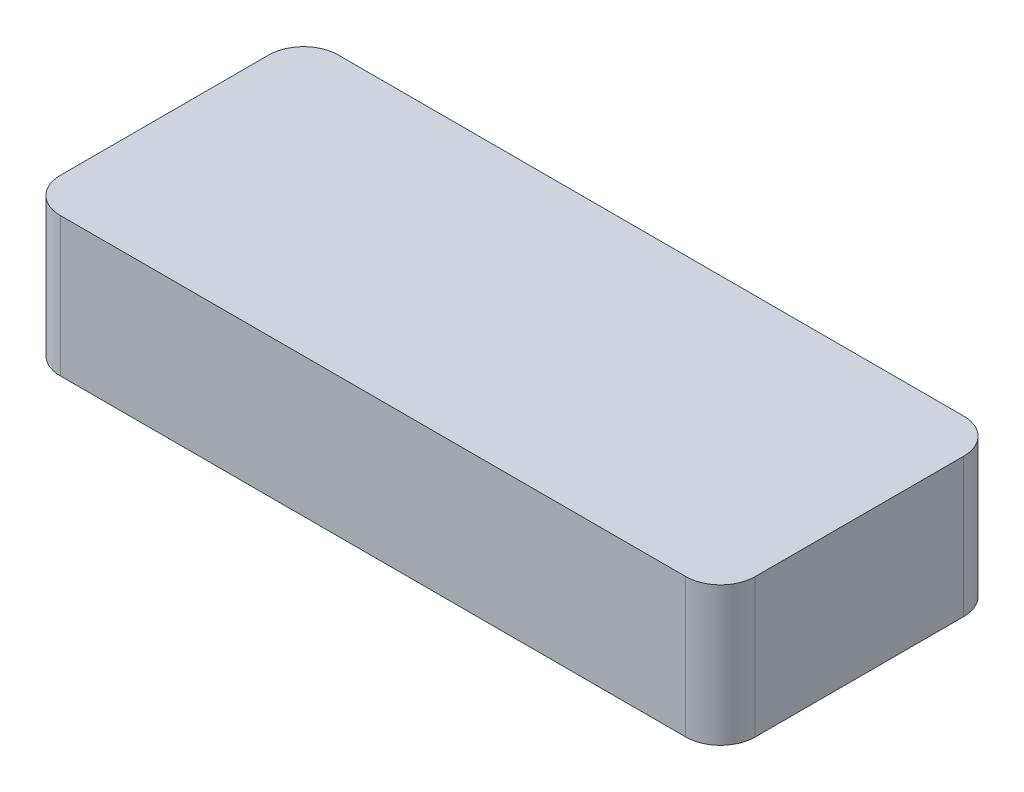
SolidWorks part; units mm, degrees
ref_plane "Front Plane" through (0, 0, 0) normal (0, 0, 1) x (1, 0, 0)
ref_plane "Top Plane" through (0, 0, 0) normal (0, 1, 0) x (1, 0, 0)
ref_plane "Right Plane" through (0, 0, 0) normal (1, 0, 0) x (0, 0, -1)
sketch "Sketch1" plane through (0, 0, 0) normal (0, 1, 0) x (1, 0, 0)
  line L1 (-15.875, 6.35) -> (15.875, 6.35)
  line L2 (-15.875, 6.35) -> (-15.875, -6.35)
  line L3 (-15.875, -6.35) -> (15.875, -6.35)
  line L4 (15.875, 6.35) -> (15.875, -6.35)
  line L5 (-15.875, 6.35) -> (15.875, -6.35) construction
  line L6 (-15.875, -6.35) -> (15.875, 6.35) construction
  point P0 (0, 0)
  dimension "D1" = 31.75
  dimension "D2" = 12.7
extrude "Boss-Extrude1" add sketch "Sketch1" along normal blind 6.35
fillet "Fillet1" radius 1.5875 4 edges at (-15.875, 3.175, -6.35) (-15.875, 3.175, 6.35) (15.875, 3.175, -6.35) (15.875, 3.175, 6.35)
